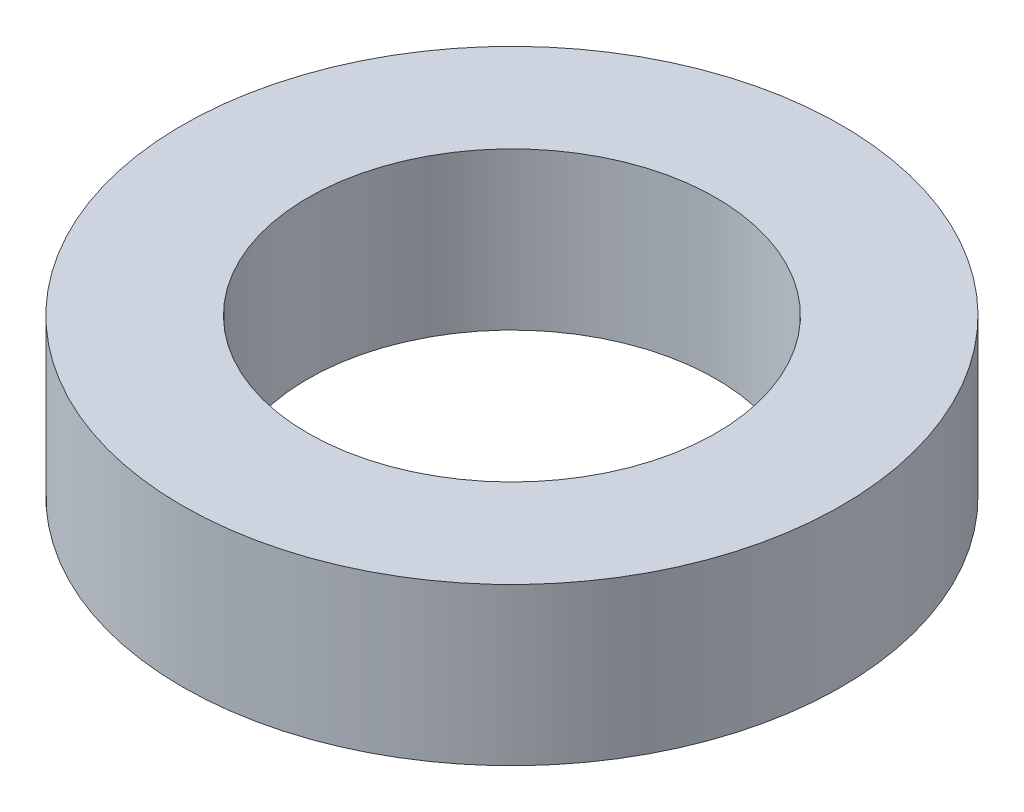
SolidWorks part; units mm, degrees
ref_plane "Спереди" through (0, 0, 0) normal (0, 0, 1) x (1, 0, 0)
ref_plane "Сверху" through (0, 0, 0) normal (0, 1, 0) x (1, 0, 0)
ref_plane "Справа" through (0, 0, 0) normal (1, 0, 0) x (0, 0, -1)
sketch "Эскиз1" plane through (0, 0, 0) normal (0, 1, 0) x (1, 0, 0)
  circle A0 centre (0, 0) radius 10.5
  circle A1 centre (0, 0) radius 6.5
extrude "Бобышка-Вытянуть1" add sketch "Эскиз1" along normal blind 5
